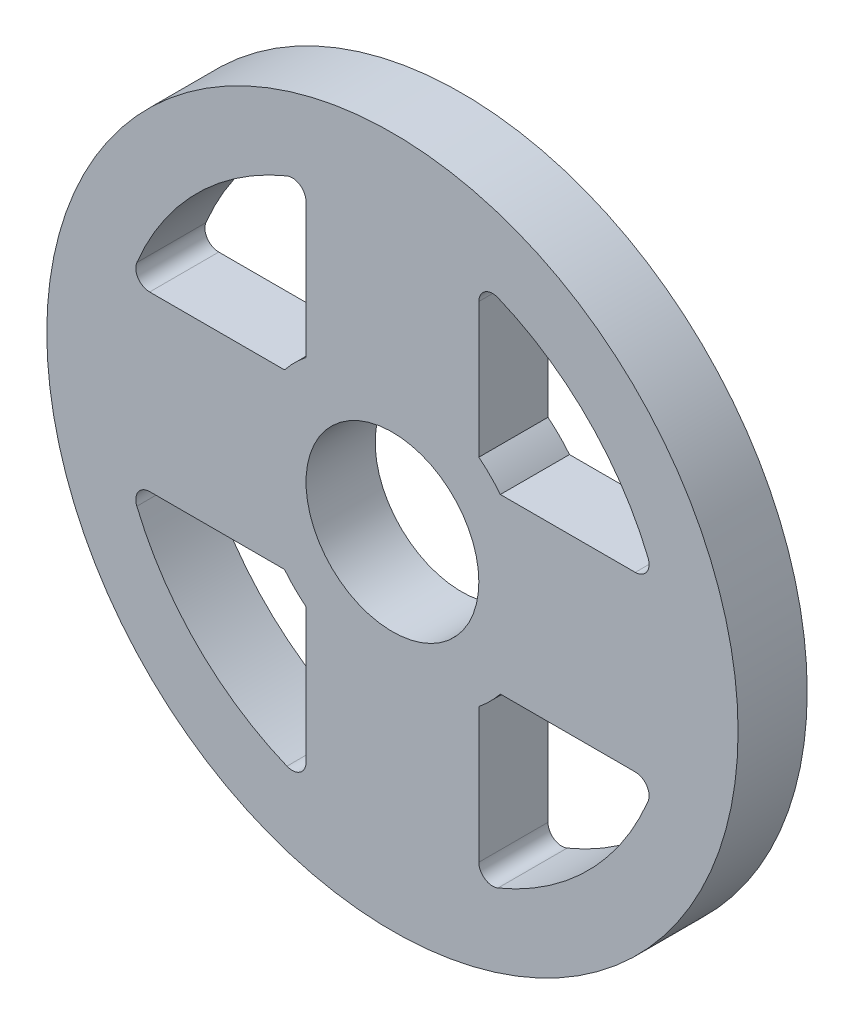
SolidWorks part; units mm, degrees
ref_plane "Front Plane" through (0, 0, 0) normal (0, 0, 1) x (1, 0, 0)
ref_plane "Top Plane" through (0, 0, 0) normal (0, 1, 0) x (1, 0, 0)
ref_plane "Right Plane" through (0, 0, 0) normal (1, 0, 0) x (0, 0, -1)
sketch "Sketch1" plane through (0, 0, 0) normal (0, 0, 1) x (1, 0, 0)
  line L0 (0, 6.25) -> (0, -6.25)
  line L1 (7.8062, 6.25) -> (17.5624, 6.25)
  line L4 (6.25, 0) -> (-6.25, 0)
  line L7 (-6.25, -7.8062) -> (-6.25, -17.5624)
  line L8 (0, -6.25) -> (0, 6.25)
  line L9 (-7.8062, -6.25) -> (-17.5624, -6.25)
  line L11 (-7.8062, 6.25) -> (-17.5624, 6.25)
  line L12 (-6.25, 0) -> (6.25, 0)
  line L13 (-6.25, 7.8062) -> (-6.25, 17.5624)
  line L15 (6.25, 7.8062) -> (6.25, 17.5624)
  line L16 (6.25, -7.8062) -> (6.25, -17.5624)
  line L17 (7.8062, -6.25) -> (17.5624, -6.25)
  line L18 (6.25, 0) -> (6.25, -6.25) [skipped]
  circle A0 centre (0, 0) radius 25
  arc A1 (18.4867, 7.6316) -> (7.6316, 18.4867) centre (0, 0) ccw
  circle A2 centre (0, 0) radius 10
  circle A3 centre (0, 0) radius 6.25
  arc A4 (7.6316, -18.4867) -> (18.4867, -7.6316) centre (0, 0) ccw
  arc A5 (-18.4867, -7.6316) -> (-7.6316, -18.4867) centre (0, 0) ccw
  arc A6 (-7.6316, 18.4867) -> (-18.4867, 7.6316) centre (0, 0) ccw
  arc A7 (18.4867, -7.6316) -> (17.5624, -6.25) centre (17.5624, -7.25) ccw
  arc A8 (6.25, -17.5624) -> (7.6316, -18.4867) centre (7.25, -17.5624) ccw
  arc A9 (-7.6316, -18.4867) -> (-6.25, -17.5624) centre (-7.25, -17.5624) ccw
  arc A10 (-18.4867, -7.6316) -> (-17.5624, -6.25) centre (-17.5624, -7.25) cw
  arc A11 (-17.5624, 6.25) -> (-18.4867, 7.6316) centre (-17.5624, 7.25) cw
  arc A12 (-6.25, 17.5624) -> (-7.6316, 18.4867) centre (-7.25, 17.5624) ccw
  arc A13 (7.6316, 18.4867) -> (6.25, 17.5624) centre (7.25, 17.5624) ccw
  arc A14 (18.4867, 7.6316) -> (17.5624, 6.25) centre (17.5624, 7.25) cw
  point P25 (0, 0)
  point P26 (6.25, -18.9984)
  point P35 (-6.25, 18.9984)
  dimension "D1" = 50
  dimension "D2" = 40
  dimension "D3" = 20
  dimension "D4" = 12.5
  dimension "D6" = 1
  dimension "D5" = 4
extrude "Boss-Extrude1" add sketch "Sketch1" along normal blind 5 contours A0 A1 A14 L1 A2 L17 A7 A4 A8 L16 L7 A9 A5 A10 L9 L11 A11 A6 A12 L13 L15 A13 | A2 A3
